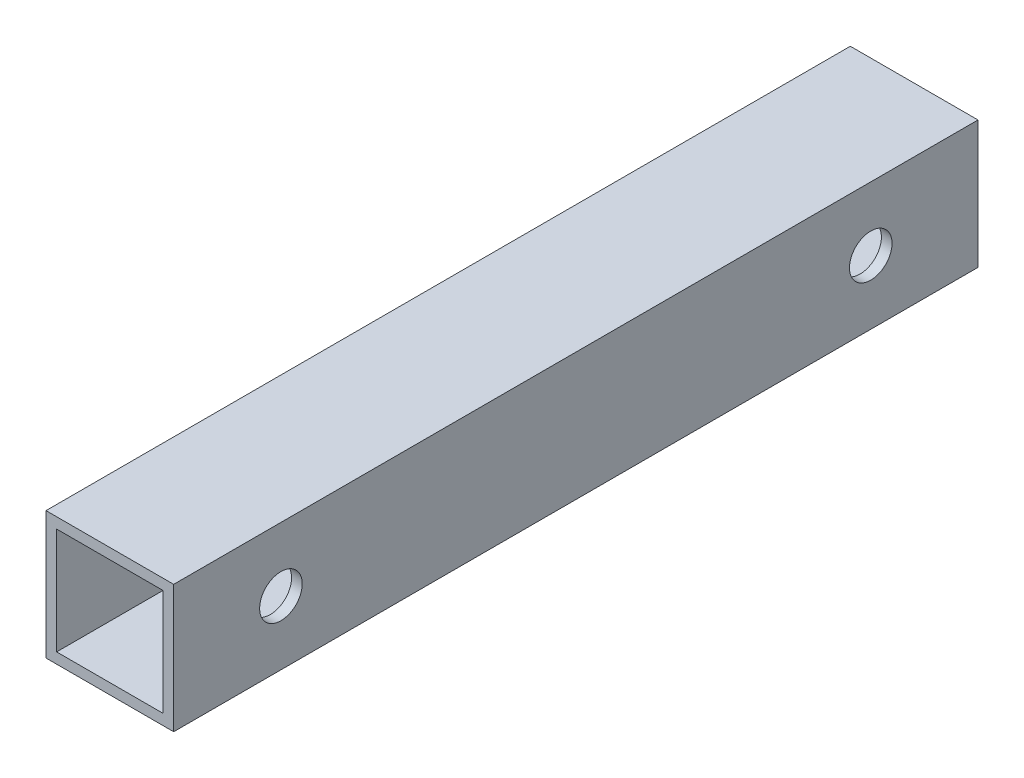
SolidWorks part; units mm, degrees
material "Brass"
ref_plane "Front Plane" through (0, 0, 0) normal (0, 0, 1) x (1, 0, 0)
ref_plane "Top Plane" through (0, 0, 0) normal (0, 1, 0) x (1, 0, 0)
ref_plane "Right Plane" through (0, 0, 0) normal (1, 0, 0) x (0, 0, -1)
sketch "Sketch1" plane through (0, 0, 0) normal (0, 0, 1) x (1, 0, 0)
  line L1 (-2.3813, -2.3813) -> (2.3812, -2.3813)
  line L2 (-2.3813, -2.3813) -> (-2.3813, 2.3812)
  line L3 (-2.3813, 2.3812) -> (2.3812, 2.3812)
  line L4 (2.3812, -2.3813) -> (2.3812, 2.3812)
  line L5 (-2.3813, -2.3813) -> (2.3812, 2.3812) construction
  line L6 (-2.3813, 2.3812) -> (2.3812, -2.3813) construction
  line L7 (-1.9844, -1.9844) -> (1.9844, -1.9844)
  line L8 (-1.9844, -1.9844) -> (-1.9844, 1.9844)
  line L9 (-1.9844, 1.9844) -> (1.9844, 1.9844)
  line L10 (1.9844, -1.9844) -> (1.9844, 1.9844)
  line L11 (-1.9844, -1.9844) -> (1.9844, 1.9844) construction
  line L12 (-1.9844, 1.9844) -> (1.9844, -1.9844) construction
  point P0 (0, 0)
  point P6 (0, 0)
  dimension "D1" = 4.7625
  dimension "D2" = 4.7625
  dimension "D3" = 1.9844
extrude "Boss-Extrude1" add sketch "Sketch1" along normal mid plane 30
sketch "Sketch2" plane through (-2.3813, 0, 0) normal (-1, 0, 0) x (0, 0, 1)
  line L0 (-15, 2.3812) -> (-15, -2.3813) construction
  line L1 (15, 2.3812) -> (15, -2.3813) construction
  circle A0 centre (-11, 0) radius 0.7937
  circle A1 centre (11, 0) radius 0.7937
  point P6 (-15, 0)
  dimension "D1" = 1.5875
  dimension "D2" = 4
  dimension "D3" = 4
extrude "Cut-Extrude1" cut sketch "Sketch2" against normal through all
sketch "Sketch3" plane through (0, 0, 0) normal (0, 1, 0) x (1, 0, 0)
  line L0 (0, 15) -> (0, -15) construction
  line L1 (2.3812, 15) -> (-2.3813, 15) construction
  line L2 (2.3812, -15) -> (-2.3813, -15) construction
